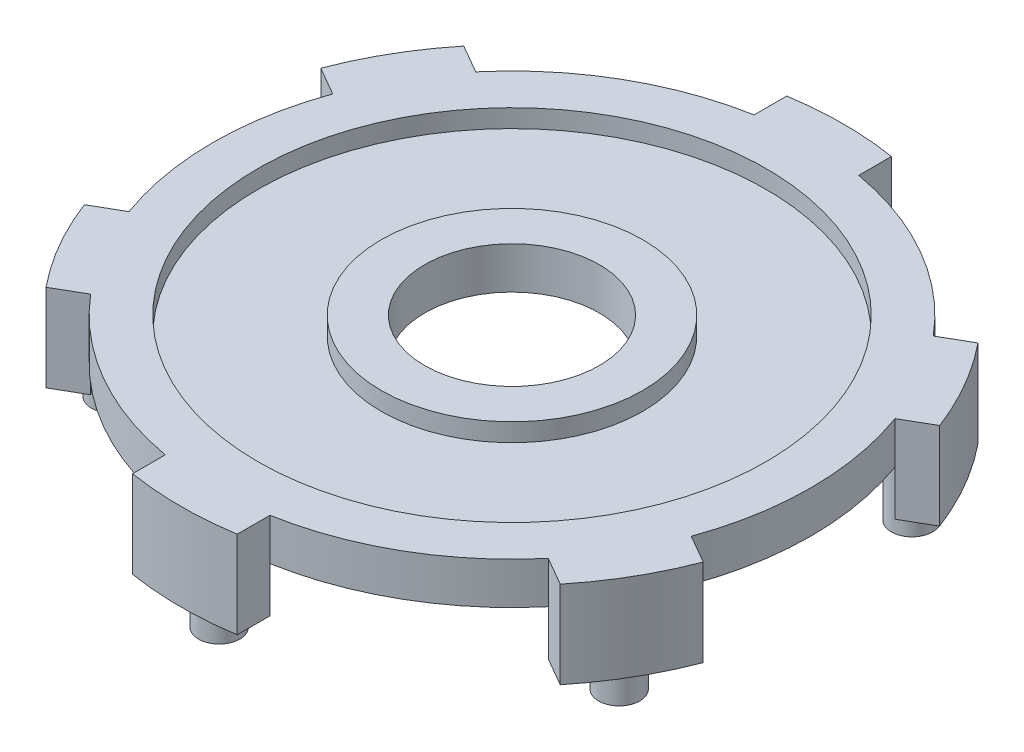
SolidWorks part; units mm, degrees
material "ABS"
ref_plane "Front Plane" through (0, 0, 0) normal (0, 0, 1) x (1, 0, 0)
ref_plane "Top Plane" through (0, 0, 0) normal (0, 1, 0) x (1, 0, 0)
ref_plane "Right Plane" through (0, 0, 0) normal (1, 0, 0) x (0, 0, -1)
sketch "Sketch1" plane through (0, 0, 0) normal (0, 1, 0) x (1, 0, 0)
  circle A0 centre (0, 0) radius 13.4239
  dimension "D1" = 26.8478
extrude "Boss-Extrude1" add sketch "Sketch1" along normal blind 1.8796
sketch "Sketch2" plane through (0, 1.8796, 0) normal (0, 1, 0) x (1, 0, 0)
  line L0 (-13.8923, 5.3077) -> (-4.699, 0)
  line L2 (2.3495, -14.6849) -> (2.3495, -4.0695)
  line L4 (-2.3495, -14.6849) -> (-2.3495, -4.0695)
  line L7 (-11.5428, 9.3772) -> (-2.3495, 4.0695)
  line L8 (11.5428, 9.3772) -> (2.3495, 4.0695)
  line L9 (13.8923, 5.3077) -> (4.699, 0)
  line L10 (2.3495, 4.0695) -> (2.3495, 14.6849)
  line L11 (4.699, 0) -> (13.8923, -5.3077)
  line L12 (-2.3495, 4.0695) -> (-2.3495, 14.6849)
  line L14 (-4.699, 0) -> (-13.8923, -5.3077)
  line L15 (-2.3495, -4.0695) -> (-11.5428, -9.3772)
  line L16 (2.3495, -4.0695) -> (11.5428, -9.3772)
  arc A0 (-2.3495, -14.6849) -> (2.3495, -14.6849) centre (0, 0) ccw
  arc A1 (2.3495, 14.6849) -> (-2.3495, 14.6849) centre (0, 0) ccw
  arc A2 (11.5428, -9.3772) -> (13.8923, -5.3077) centre (0, 0) ccw
  arc A3 (-11.5428, 9.3772) -> (-13.8923, 5.3077) centre (0, 0) ccw
  arc A4 (-13.8923, -5.3077) -> (-11.5428, -9.3772) centre (0, 0) ccw
  arc A5 (13.8923, 5.3077) -> (11.5428, 9.3772) centre (0, 0) ccw
  point P0 (0, 0)
  point P18 (0, 0)
  point P22 (0, 0)
  point P23 (0, 0)
  point P25 (0, 0)
  point P26 (0, 0)
  point P27 (0, 0)
  point P29 (0, 0)
  point P30 (0, 0)
  dimension "D2" = 14.6849
  dimension "D1" = 4.699
  dimension "D5" = 4.699
  dimension "D3" = 3
extrude "Boss-Extrude2" add sketch "Sketch2" against normal blind 1.8796
sketch "Sketch3" plane through (0, 1.8796, 0) normal (0, 1, 0) x (1, 0, 0)
  circle A0 centre (0, 0) radius 11.4046
  circle A1 centre (0, 0) radius 5.8674
  dimension "D1" = 22.8092
  dimension "D2" = 11.7348
extrude "Cut-Extrude1" cut sketch "Sketch3" against normal blind 0.8128 contours A0
sketch "Sketch4" plane through (0, 1.0668, 0) normal (0, 1, 0) x (1, 0, 0)
  circle A0 centre (0, 0) radius 5.8674
  dimension "D1" = 11.7348
extrude "Boss-Extrude3" add sketch "Sketch4" along normal up to surface (0.8128 mm away) up to face at (0, 1.8796, 11.4046)
sketch "Sketch5" plane through (0, 1.8796, 0) normal (0, 1, 0) x (1, 0, 0)
  circle A0 centre (0, 0) radius 3.9243
  dimension "D1" = 7.8486
extrude "Cut-Extrude2" cut sketch "Sketch5" against normal through all
sketch "Sketch6" plane through (0, 0, 0) normal (0, -1, 0) x (1, 0, 0)
  circle A0 centre (0, 0) radius 7.7216
  dimension "D1" = 15.4432
extrude "Boss-Extrude4" add sketch "Sketch6" along normal blind 1.778
sketch "Sketch7" plane through (0, -1.778, 0) normal (0, -1, 0) x (1, 0, 0)
  circle A0 centre (0, 0) radius 6.5532
  dimension "D1" = 13.1064
extrude "Cut-Extrude3" cut sketch "Sketch7" against normal blind 1.778
sketch "Sketch8" plane through (0, 0, 0) normal (0, -1, 0) x (1, 0, 0)
  line L12 (-2.3495, -13.2167) -> (-2.3495, -14.6849)
  line L13 (2.3495, -14.6849) -> (2.3495, -13.2167)
  line L14 (10.2712, -8.6431) -> (11.5428, -9.3772)
  line L15 (13.8923, -5.3077) -> (12.6207, -4.5736)
  line L16 (12.6207, 4.5736) -> (13.8923, 5.3077)
  line L17 (11.5428, 9.3772) -> (10.2712, 8.6431)
  line L18 (2.3495, 13.2167) -> (2.3495, 14.6849)
  line L19 (-2.3495, 14.6849) -> (-2.3495, 13.2167)
  line L20 (-10.2712, 8.6431) -> (-11.5428, 9.3772)
  line L21 (-13.8923, 5.3077) -> (-12.6207, 4.5736)
  line L22 (-12.6207, -4.5736) -> (-13.8923, -5.3077)
  line L23 (-11.5428, -9.3772) -> (-10.2712, -8.6431)
  line L24 (-2.3495, -13.2167) -> (-2.3495, -14.6849)
  line L25 (2.3495, -14.6849) -> (2.3495, -13.2167)
  line L26 (10.2712, -8.6431) -> (11.5428, -9.3772)
  line L27 (13.8923, -5.3077) -> (12.6207, -4.5736)
  line L28 (12.6207, 4.5736) -> (13.8923, 5.3077)
  line L29 (11.5428, 9.3772) -> (10.2712, 8.6431)
  line L30 (2.3495, 13.2167) -> (2.3495, 14.6849)
  line L31 (-2.3495, 14.6849) -> (-2.3495, 13.2167)
  line L32 (-10.2712, 8.6431) -> (-11.5428, 9.3772)
  line L33 (-13.8923, 5.3077) -> (-12.6207, 4.5736)
  line L34 (-12.6207, -4.5736) -> (-13.8923, -5.3077)
  line L35 (-11.5428, -9.3772) -> (-10.2712, -8.6431)
  arc A0 (-10.2712, 8.6431) -> (-12.6207, 4.5736) centre (0, 0) ccw
  arc A1 (-2.3495, 13.2167) -> (-10.2712, 8.6431) centre (0, 0) ccw construction
  arc A2 (2.3495, 13.2167) -> (-2.3495, 13.2167) centre (0, 0) ccw
  arc A3 (12.6207, 4.5736) -> (10.2712, 8.6431) centre (0, 0) ccw
  arc A4 (10.2712, -8.6431) -> (12.6207, -4.5736) centre (0, 0) ccw
  arc A5 (-2.3495, -13.2167) -> (2.3495, -13.2167) centre (0, 0) ccw
  arc A6 (-12.6207, -4.5736) -> (-10.2712, -8.6431) centre (0, 0) ccw
  arc A14 (-10.2712, -8.6431) -> (-2.3495, -13.2167) centre (0, 0) ccw
  arc A15 (-2.3495, -14.6849) -> (2.3495, -14.6849) centre (0, 0) ccw
  arc A16 (2.3495, -13.2167) -> (10.2712, -8.6431) centre (0, 0) ccw
  arc A17 (11.5428, -9.3772) -> (13.8923, -5.3077) centre (0, 0) ccw
  arc A18 (12.6207, -4.5736) -> (12.6207, 4.5736) centre (0, 0) ccw
  arc A19 (13.8923, 5.3077) -> (11.5428, 9.3772) centre (0, 0) ccw
  arc A20 (10.2712, 8.6431) -> (2.3495, 13.2167) centre (0, 0) ccw
  arc A21 (2.3495, 14.6849) -> (-2.3495, 14.6849) centre (0, 0) ccw
  arc A22 (-2.3495, 13.2167) -> (-10.2712, 8.6431) centre (0, 0) ccw
  arc A23 (-11.5428, 9.3772) -> (-13.8923, 5.3077) centre (0, 0) ccw
  arc A24 (-12.6207, 4.5736) -> (-12.6207, -4.5736) centre (0, 0) ccw
  arc A25 (-13.8923, -5.3077) -> (-11.5428, -9.3772) centre (0, 0) ccw
  arc A27 (-2.3495, -14.6849) -> (2.3495, -14.6849) centre (0, 0) ccw
  arc A29 (11.5428, -9.3772) -> (13.8923, -5.3077) centre (0, 0) ccw
  arc A31 (13.8923, 5.3077) -> (11.5428, 9.3772) centre (0, 0) ccw
  arc A33 (2.3495, 14.6849) -> (-2.3495, 14.6849) centre (0, 0) ccw
  arc A35 (-11.5428, 9.3772) -> (-13.8923, 5.3077) centre (0, 0) ccw
  arc A37 (-13.8923, -5.3077) -> (-11.5428, -9.3772) centre (0, 0) ccw
  dimension "D1" = 0
extrude "Boss-Extrude5" add sketch "Sketch8" along normal blind 2.032
sketch "Sketch9" plane through (0, 0, 0) normal (0, -1, 0) x (1, 0, 0)
  line L1 (-11.3835, -6.5722) -> (11.3835, 6.5723) construction
  line L2 (0, 13.1445) -> (0, -13.1445) construction
  circle A0 centre (0, 0) radius 13.1445 construction
  circle A1 centre (0, 13.1445) radius 0.9271
  arc A2 (12.6207, 4.5736) -> (10.2712, 8.6431) centre (0, 0) ccw construction
  point P17 (11.6254, 6.7119)
  point P19 (0, 0)
  point P23 (0, 0)
  dimension "D1" = 26.289
  dimension "D2" = 1.8542
  dimension "D5" = 60
extrude "Boss-Extrude6" add sketch "Sketch9" along normal blind 3.683
pattern_circular "CirPattern1" count 6 over 360 about axis through (0, 0, 0) along (0, 1, 0) of "Boss-Extrude6"
